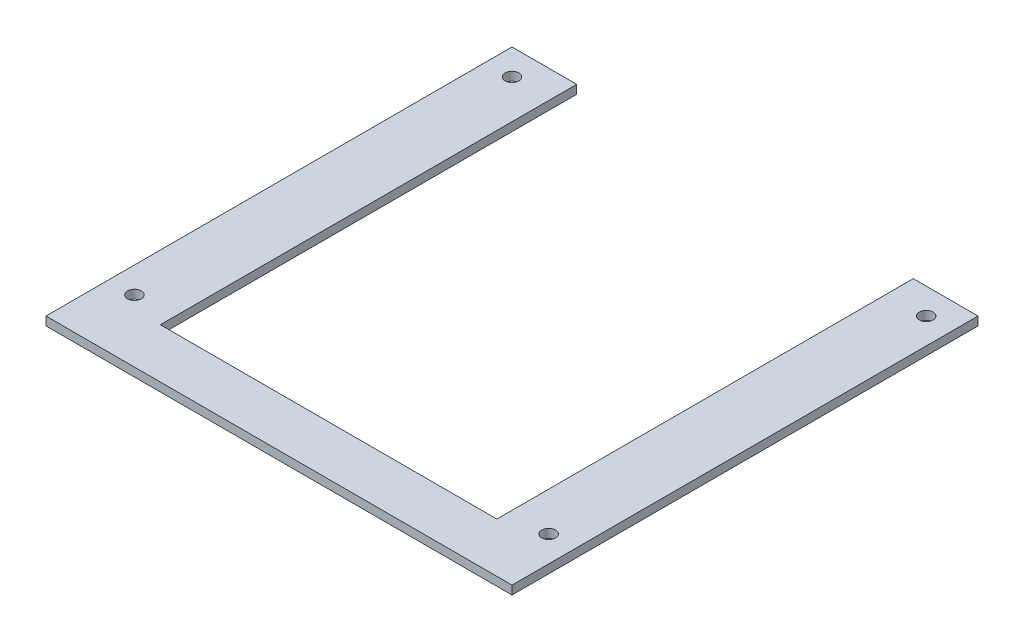
SolidWorks part; units mm, degrees
ref_plane "前视基准面" through (0, 0, 0) normal (0, 0, 1) x (1, 0, 0)
ref_plane "上视基准面" through (0, 0, 0) normal (0, 1, 0) x (1, 0, 0)
ref_plane "右视基准面" through (0, 0, 0) normal (1, 0, 0) x (0, 0, -1)
sketch "草图1" plane through (0, 0, 0) normal (0, 1, 0) x (1, 0, 0)
  line L1 (-57.0171, 35.704) -> (50.9829, 35.704)
  line L2 (-57.0171, 35.704) -> (-57.0171, -72.296)
  line L3 (-57.0171, -72.296) -> (50.9829, -72.296)
  line L4 (50.9829, 35.704) -> (50.9829, -72.296)
  dimension "D1" = 108
  dimension "D2" = 108
extrude "凸台-拉伸1" add sketch "草图1" along normal blind 2
sketch "草图2" plane through (0, 2, 0) normal (0, 1, 0) x (1, 0, 0)
  line L0 (50.9829, 35.704) -> (-57.0171, 35.704) construction
  line L1 (-42.0171, 35.704) -> (35.9829, 35.704)
  line L2 (-42.0171, 35.704) -> (-42.0171, -60.796)
  line L3 (-42.0171, -60.796) -> (35.9829, -60.796)
  line L4 (35.9829, 35.704) -> (35.9829, -60.796)
  line L5 (-57.0171, -72.296) -> (50.9829, -72.296) construction
  circle A0 centre (-51.0171, 29.704) radius 1.6
  circle A1 centre (44.9829, 29.704) radius 1.6
  circle A2 centre (-51.0171, -57.796) radius 1.6
  circle A3 centre (44.9829, -57.796) radius 1.6
  point P6 (-3.0171, -60.796)
  point P7 (-3.0171, -72.296)
  point P18 (0, 0)
  point P19 (0, 0)
  point P20 (0, 0)
  point P21 (0, 0)
  point P24 (-47.7547, 35.704)
  dimension "D3" = 96
  dimension "D1" = 78
  dimension "D2" = 96.5
  dimension "D4" = 9
  dimension "D5" = 6
  dimension "D6" = 87.5
extrude "切除-拉伸1" cut sketch "草图2" against normal blind 2
